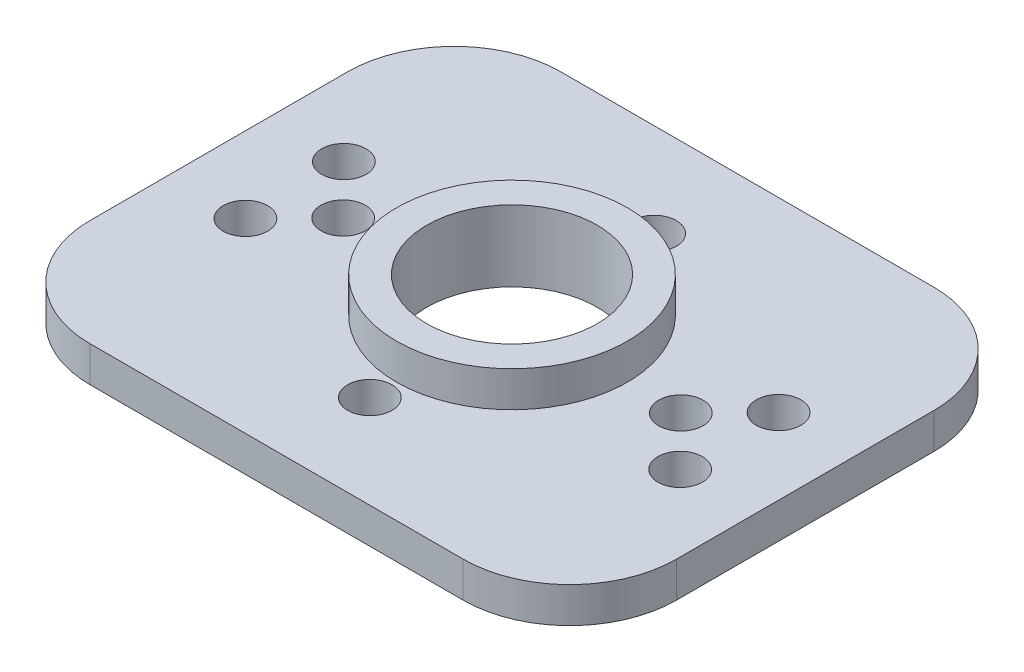
SolidWorks part; units mm, degrees
ref_plane "前视基准面" through (0, 0, 0) normal (0, 0, 1) x (1, 0, 0)
ref_plane "上视基准面" through (0, 0, 0) normal (0, 1, 0) x (1, 0, 0)
ref_plane "右视基准面" through (0, 0, 0) normal (1, 0, 0) x (0, 0, -1)
sketch "草图1" plane through (0, 0, 0) normal (0, 1, 0) x (1, 0, 0)
  line L1 (10.5, -13.247) -> (-10.5, -13.247)
  line L2 (16.5, -7.247) -> (16.5, 7.247)
  line L3 (10.5, 13.247) -> (-10.5, 13.247)
  line L4 (-16.5, -7.247) -> (-16.5, 7.247)
  line L5 (16.5, -13.247) -> (-16.5, 13.247) construction
  line L6 (16.5, 13.247) -> (-16.5, -13.247) construction
  circle A1 centre (0, 8) radius 1.25
  circle A2 centre (0, -8) radius 1.25
  circle A3 centre (-9.5, 0) radius 1.25
  circle A4 centre (9.5, 0) radius 1.25
  circle A5 centre (0, 0) radius 4.8
  arc A6 (-10.5, -13.247) -> (-16.5, -7.247) centre (-10.5, -7.247) cw
  arc A7 (10.5, -13.247) -> (16.5, -7.247) centre (10.5, -7.247) ccw
  arc A8 (10.5, 13.247) -> (16.5, 7.247) centre (10.5, 7.247) cw
  arc A9 (-16.5, 7.247) -> (-10.5, 13.247) centre (-10.5, 7.247) cw
  dimension "D1" = 8
  dimension "D4" = 33
  dimension "D5" = 6
  dimension "D2" = 9.5
  dimension "D3" = 9.5
extrude "凸台-拉伸1" add sketch "草图1" along normal blind 2
sketch "草图3" plane through (0, 2, 0) normal (0, 1, 0) x (1, 0, 0)
  circle A1 centre (0, 0) radius 4.8
  circle A2 centre (0, 0) radius 6.5
extrude "凸台-拉伸2" add sketch "草图3" along normal blind 2
sketch "草图5" plane through (0, 2, 0) normal (0, 1, 0) x (1, 0, 0)
  line L0 (0, 0) -> (12.23, 0)
  line L1 (0, 0) -> (-12.23, 0)
  line L2 (-12.23, -2.77) -> (-12.23, 2.77)
  line L3 (12.23, -2.77) -> (12.23, 2.77)
  circle A0 centre (-12.23, 2.77) radius 1.25
  circle A1 centre (-12.23, -2.77) radius 1.25
  circle A2 centre (12.23, -2.77) radius 1.25
  circle A3 centre (12.23, 2.77) radius 1.25
  point P7 (-12.23, 0)
  point P10 (12.23, 0)
extrude "切除-拉伸1" cut sketch "草图5" against normal blind 10
